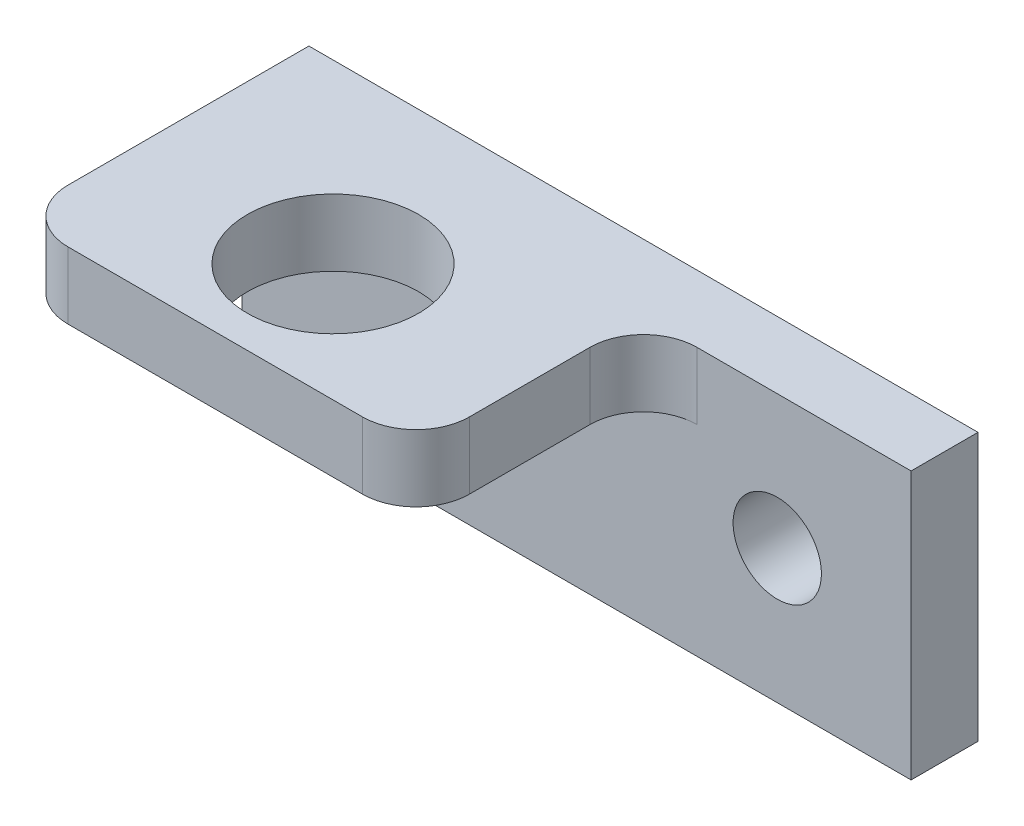
SolidWorks part; units mm, degrees
ref_plane "Ebene vorne" through (0, 0, 0) normal (0, 0, 1) x (1, 0, 0)
ref_plane "Ebene oben" through (0, 0, 0) normal (0, 1, 0) x (1, 0, 0)
ref_plane "Ebene rechts" through (0, 0, 0) normal (1, 0, 0) x (0, 0, -1)
sketch "Skizze1" plane through (0, 0, 0) normal (0, 0, 1) x (1, 0, 0)
  line L0 (25, 5) -> (0, 5) construction
  line L1 (0, 0) -> (25, 0)
  line L2 (0, 0) -> (0, 10)
  line L3 (0, 10) -> (25, 10)
  line L4 (25, 0) -> (25, 10)
  circle A0 centre (20, 5) radius 1.65
  point P9 (0, 0)
  dimension "D3" = 3.3
  dimension "D1" = 10
  dimension "D2" = 25
  dimension "D4" = 5
extrude "Aufsatz-Linear austragen1" add sketch "Skizze1" along normal blind 2.5
sketch "Skizze2" plane through (0, 0, 2.5) normal (0, 0, 1) x (1, 0, 0)
  line L0 (25, 10) -> (0, 10) construction
  line L1 (0, 10) -> (15, 10)
  line L2 (0, 10) -> (0, 7.5)
  line L3 (0, 7.5) -> (15, 7.5)
  line L4 (15, 10) -> (15, 7.5)
  line L5 (0, -1.375) -> (0, 1.375) construction
  dimension "D1" = 2.5
  dimension "D2" = 15
extrude "Aufsatz-Linear austragen2" add sketch "Skizze2" along normal blind 8.5
fillet "Verrundung1" radius 2 3 edges at (15, 8.75, 2.5) (0, 8.75, 11) (15, 8.75, 11)
sketch "Skizze3" plane through (0, 7.5, 0) normal (0, -1, 0) x (1, 0, 0)
  line L0 (7.5, 11) -> (7.5, 2.8015) construction
  line L1 (2, 11) -> (13, 11) construction
  line L3 (0, 2.5) -> (17, 2.5) construction
  circle A0 centre (7.5, 6.6) radius 3.2
  point P6 (0, 0)
  point P9 (7.5, 5.9214)
  dimension "D2" = 6.4
  dimension "D1" = 4.1
extrude "Schnitt-Linear austragen1" cut sketch "Skizze3" against normal blind 8.5
